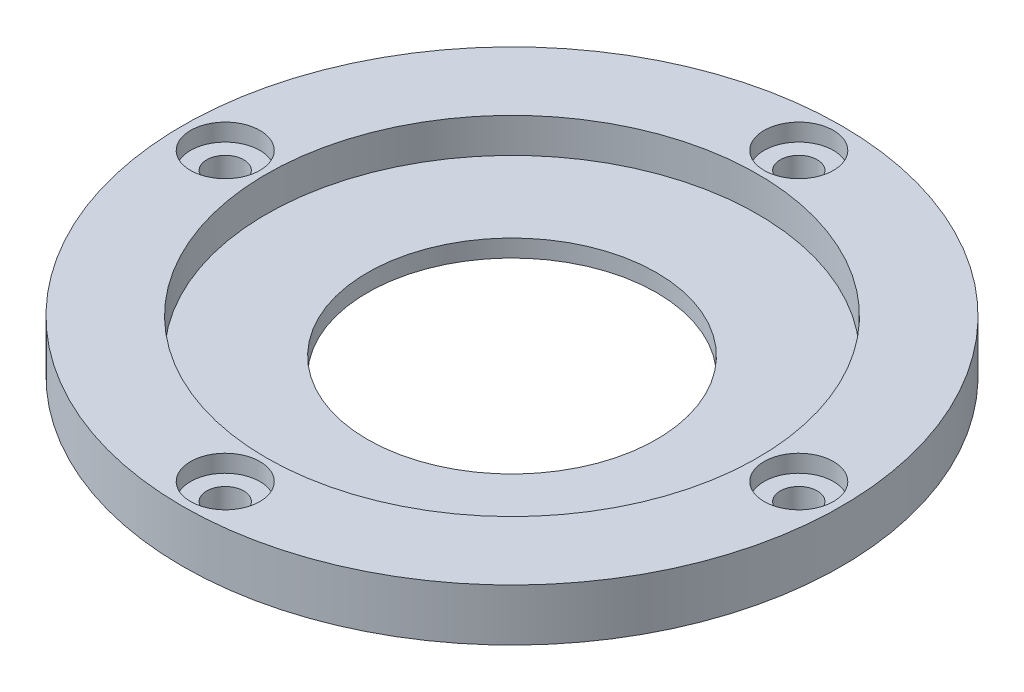
SolidWorks part; units mm, degrees
ref_plane "前视基准面" through (0, 0, 0) normal (0, 0, 1) x (1, 0, 0)
ref_plane "上视基准面" through (0, 0, 0) normal (0, 1, 0) x (1, 0, 0)
ref_plane "右视基准面" through (0, 0, 0) normal (1, 0, 0) x (0, 0, -1)
sketch "草图1" plane through (0, 0, 0) normal (0, 1, 0) x (1, 0, 0)
  circle A0 centre (0, 0) radius 12.5
  circle A1 centre (0, 0) radius 28.5
  dimension "D1" = 25
  dimension "D2" = 57
extrude "凸台-拉伸1" add sketch "草图1" along normal blind 1.5
sketch "草图2" plane through (0, 1.5, 0) normal (0, 1, 0) x (1, 0, 0)
  circle A0 centre (0, 0) radius 21.25
  circle A3 centre (0, 0) radius 28.5 construction
  circle A4 centre (0, 0) radius 28.5
  dimension "D1" = 42.5
extrude "凸台-拉伸2" add sketch "草图2" along normal blind 3
sketch "草图3" plane through (0, 4.5, 0) normal (0, 1, 0) x (1, 0, 0)
  circle A0 centre (0, 24.8) radius 3
  circle A1 centre (24.8, 0) radius 3
  circle A2 centre (0, -24.8) radius 3
  circle A3 centre (-24.8, 0) radius 3
  point P12 (0, 0)
  dimension "D1" = 6
  dimension "D2" = 24.8
  dimension "D3" = 4
extrude "切除-拉伸1" cut sketch "草图3" against normal blind 1.5
sketch "草图4" plane through (0, 3, 0) normal (0, 1, 0) x (1, 0, 0)
  circle A0 centre (0, 24.8) radius 1.6
  circle A1 centre (24.8, 0) radius 1.6
  circle A2 centre (0, -24.8) radius 1.6
  circle A3 centre (-24.8, 0) radius 1.6
  point P12 (0, 0)
  dimension "D1" = 3.2
  dimension "D2" = 4
extrude "切除-拉伸2" cut sketch "草图4" against normal through all
